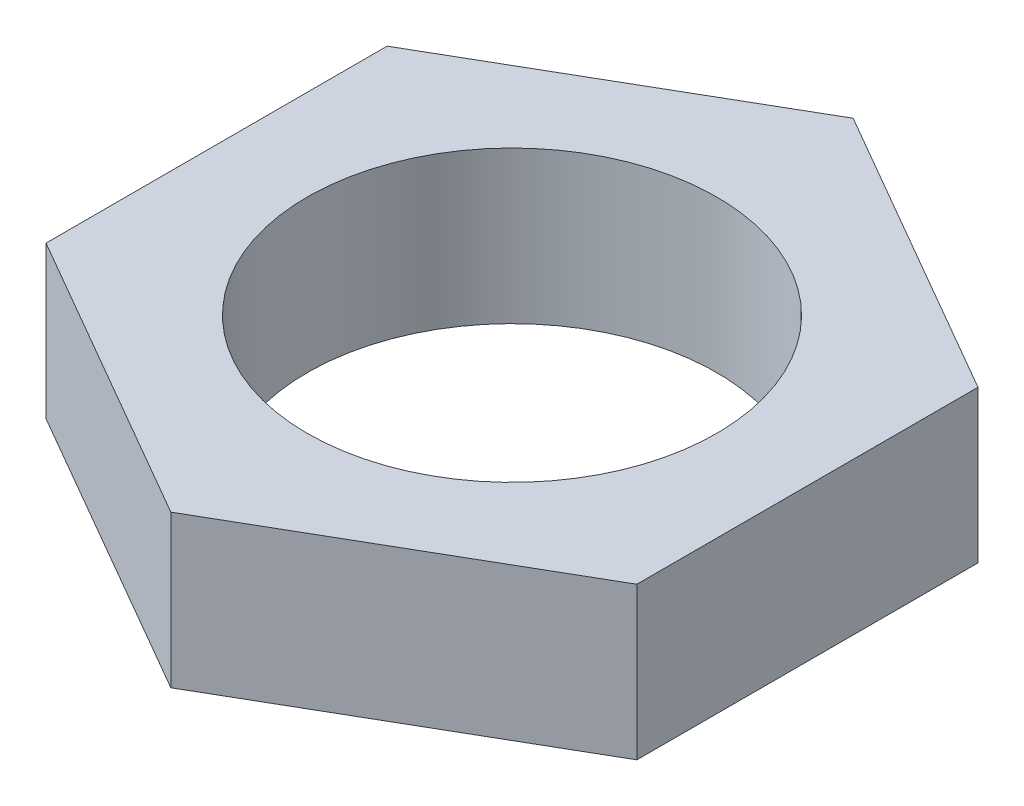
SolidWorks part; units mm, degrees
material "Plain Carbon Steel"
ref_plane "Front" through (0, 0, 0) normal (0, 0, 1) x (1, 0, 0)
ref_plane "Top" through (0, 0, 0) normal (0, 1, 0) x (1, 0, 0)
ref_plane "Right" through (0, 0, 0) normal (1, 0, 0) x (0, 0, -1)
sketch "Sketch1" plane through (0, 0, 0) normal (0, 1, 0) x (1, 0, 0)
  line L1 (0, 5.8312) -> (-5.05, 2.9156)
  line L2 (-5.05, 2.9156) -> (-5.05, -2.9156)
  line L3 (-5.05, -2.9156) -> (0, -5.8312)
  line L4 (0, -5.8312) -> (5.05, -2.9156)
  line L5 (5.05, -2.9156) -> (5.05, 2.9156)
  line L6 (5.05, 2.9156) -> (0, 5.8312)
  circle A0 centre (0, 0) radius 5.05 construction
  dimension "D1" = 10.1
extrude "Boss-Extrude1" add sketch "Sketch1" along normal blind 2.6
sketch "Sketch2" plane through (0, 2.6, 0) normal (0, 1, 0) x (1, 0, 0)
  circle A0 centre (0, 0) radius 3.5
  dimension "D1" = 7
extrude "Cut-Extrude1" cut sketch "Sketch2" against normal through all
